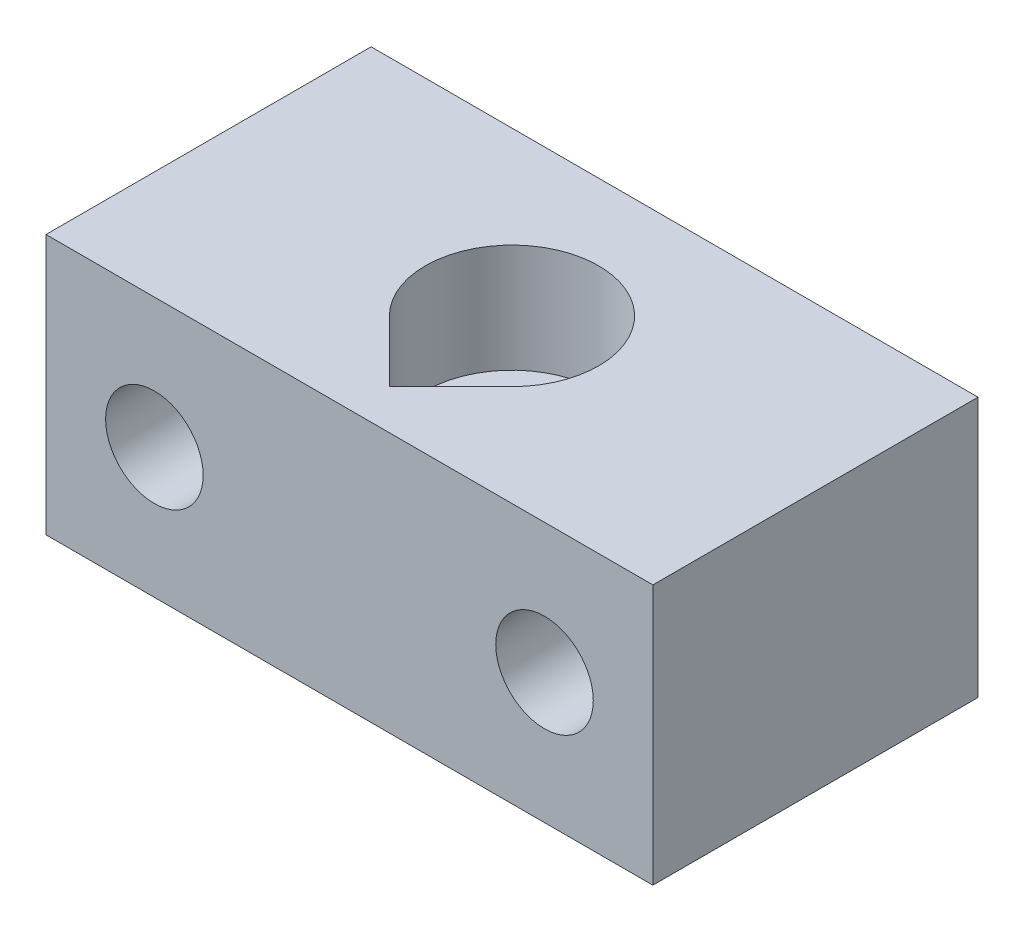
SolidWorks part; units mm, degrees
material "Printed PLA"
ref_plane "Front Plane" through (0, 0, 0) normal (0, 0, 1) x (1, 0, 0)
ref_plane "Top Plane" through (0, 0, 0) normal (0, 1, 0) x (1, 0, 0)
ref_plane "Right Plane" through (0, 0, 0) normal (1, 0, 0) x (0, 0, -1)
sketch "Sketch1" plane through (0, 0, 0) normal (0, 1, 0) x (1, 0, 0)
  line L0 (-14, 15) -> (14, -15) construction
  line L1 (-14, 15) -> (14, 15)
  line L2 (-14, 15) -> (-14, -15)
  line L3 (-14, -15) -> (14, -15)
  line L4 (14, 15) -> (14, -15)
  line L5 (0, 7.5) -> (0, -7.5) construction
  line L6 (-1.591, -9.091) -> (0, -10.682)
  line L7 (0, -10.682) -> (1.591, -9.091)
  line L8 (-1.591, 5.909) -> (0, 4.318)
  line L9 (0, 4.318) -> (1.591, 5.909)
  arc A0 (1.591, 5.909) -> (-1.591, 5.909) centre (0, 7.5) ccw
  arc A1 (1.591, -9.091) -> (-1.591, -9.091) centre (0, -7.5) ccw
  dimension "D3" = 2.25
  dimension "D1" = 28
  dimension "D2" = 30
  dimension "D4" = 15
extrude "Boss-Extrude1" add sketch "Sketch1" along normal blind 12
sketch "Sketch2" plane through (0, 0, 15) normal (0, 0, 1) x (1, 0, 0)
  line L0 (0, 0) -> (0, 6) construction
  line L1 (0, 6) -> (0, 12) construction
  line L2 (-14, 12) -> (14, 12) construction
  line L3 (-9, 6) -> (9, 6) construction
  circle A0 centre (-9, 6) radius 2.25
  circle A1 centre (9, 6) radius 2.25
  dimension "D1" = 4.5
  dimension "D2" = 18
extrude "Cut-Extrude1" cut sketch "Sketch2" against normal through all
sketch "Sketch3" plane through (0, 12, 0) normal (0, 1, 0) x (1, 0, 0)
  line L0 (-14, -15) -> (14, -15) construction
  line L1 (-4, -15) -> (4, -15)
  line L2 (0, -16.2806) -> (0, 0) construction
  arc A0 (-4, -15) -> (4, -15) centre (0, -16.2806) cw
  dimension "D2" = 4.2
  dimension "D1" = 8
extrude "Cut-Extrude2" [suppressed] cut sketch "Sketch3" against normal through all
sketch "Sketch4" plane through (0, 12, 0) normal (0, 1, 0) x (1, 0, 0)
  line L0 (-14, 15) -> (-14, -15) construction
  line L1 (-14, 0) -> (14, 0)
  line L2 (-14, 0) -> (-14, -15)
  line L3 (-14, -15) -> (14, -15)
  line L4 (14, 0) -> (14, -15)
extrude "Cut-Extrude3" cut sketch "Sketch4" against normal through all
sketch "Sketch5" plane through (0, 12, 0) normal (0, 1, 0) x (1, 0, 0)
  line L0 (-2.8284, 4.6716) -> (0, 1.8431)
  line L1 (0, 1.8431) -> (2.8284, 4.6716)
  line L2 (0, 1.8431) -> (0, 7.5) construction
  arc A0 (2.8284, 4.6716) -> (-2.8284, 4.6716) centre (0, 7.5) ccw
  dimension "D1" = 8
extrude "Cut-Extrude4" cut sketch "Sketch5" against normal blind 5
